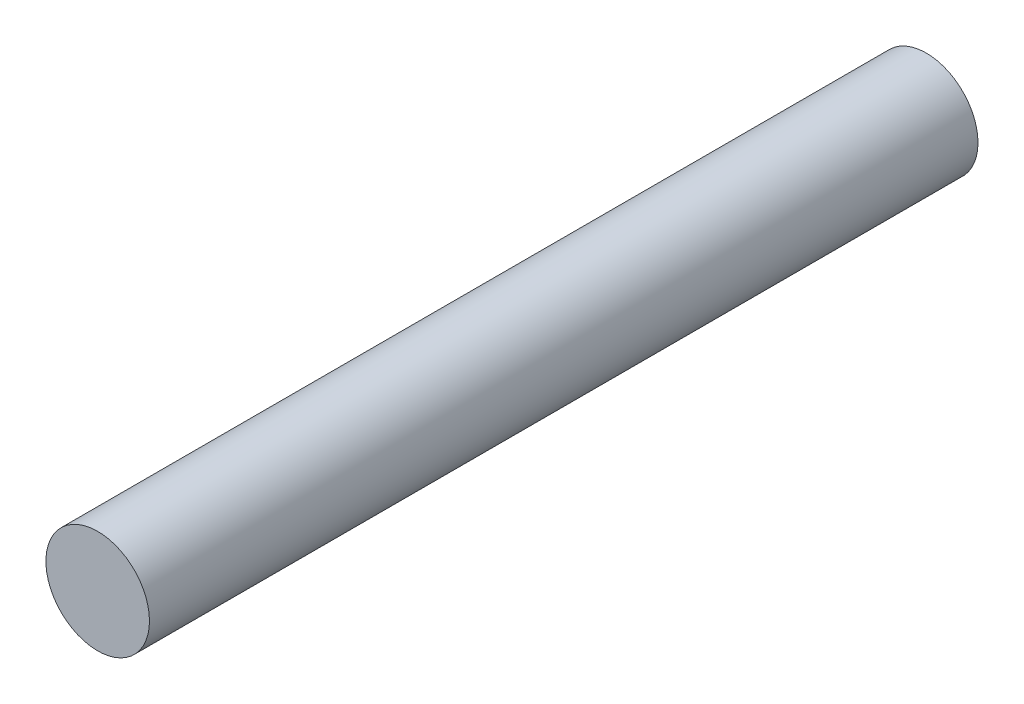
SolidWorks part; units mm, degrees
material "1.4000 (X6Cr13)"
ref_plane "Alzado" through (0, 0, 0) normal (0, 0, 1) x (1, 0, 0)
ref_plane "Planta" through (0, 0, 0) normal (0, 1, 0) x (1, 0, 0)
ref_plane "Vista lateral" through (0, 0, 0) normal (1, 0, 0) x (0, 0, -1)
sketch "Croquis1" plane through (0, 0, 0) normal (0, 0, 1) x (1, 0, 0)
  circle A0 centre (0, 0) radius 2.5
  dimension "D1" = 5
extrude "Saliente-Extruir1" add sketch "Croquis1" along normal blind 40
